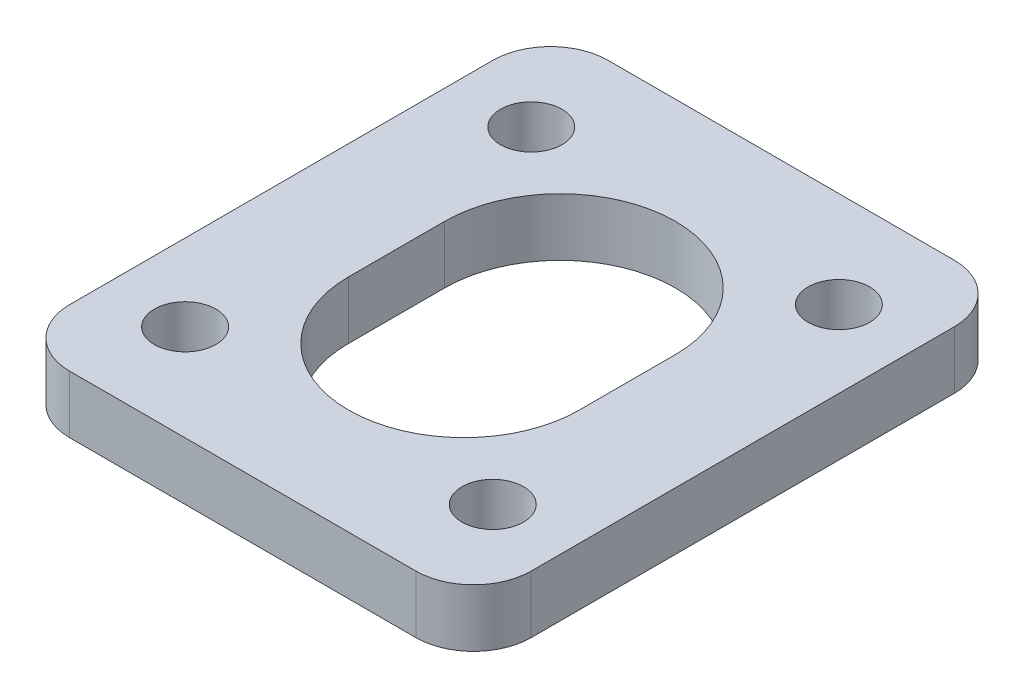
SolidWorks part; units mm, degrees
material "Thornel Mat VMA"
ref_plane "前视基准面" through (0, 0, 0) normal (0, 0, 1) x (1, 0, 0)
ref_plane "上视基准面" through (0, 0, 0) normal (0, 1, 0) x (1, 0, 0)
ref_plane "右视基准面" through (0, 0, 0) normal (1, 0, 0) x (0, 0, -1)
other "Configuration Table"
sketch "草图1" plane through (0, 0, 0) normal (0, 1, 0) x (1, 0, 0)
  line L0 (0, 2.5) -> (0, -2.5) construction
  line L1 (-8, 9) -> (8, 9) construction
  line L2 (-8, 9) -> (-8, -9) construction
  line L3 (-8, -9) -> (8, -9) construction
  line L4 (8, 9) -> (8, -9) construction
  line L5 (-8, 9) -> (8, -9) construction
  line L6 (-8, -9) -> (8, 9) construction
  line L7 (-12, 14) -> (12, 14)
  line L8 (-12, 14) -> (-12, -14)
  line L9 (-12, -14) -> (12, -14)
  line L10 (12, 14) -> (12, -14)
  line L11 (-12, 14) -> (12, -14) construction
  line L12 (-12, -14) -> (12, 14) construction
  line L13 (6, 2.5) -> (6, -2.5)
  line L14 (-6, 2.5) -> (-6, -2.5)
  circle A0 centre (8, -9) radius 1.6
  circle A1 centre (-8, -9) radius 1.6
  circle A2 centre (-8, 9) radius 1.6
  circle A3 centre (8, 9) radius 1.6
  arc A4 (6, 2.5) -> (-6, 2.5) centre (0, 2.5) ccw
  arc A5 (-6, -2.5) -> (6, -2.5) centre (0, -2.5) ccw
  point P0 (0, 0)
  point P6 (0, 0)
  point P17 (0, 0)
  dimension "D3" = 3.2
  dimension "D7" = 6
  dimension "D1" = 16
  dimension "D2" = 18
  dimension "D4" = 4
  dimension "D5" = 5
  dimension "D6" = 5
extrude "凸台-拉伸1" add sketch "草图1" along normal blind 3
fillet "圆角1" radius 3 4 edges at (-12, 1.5, 14) (-12, 1.5, -14) (12, 1.5, -14) (12, 1.5, 14)
